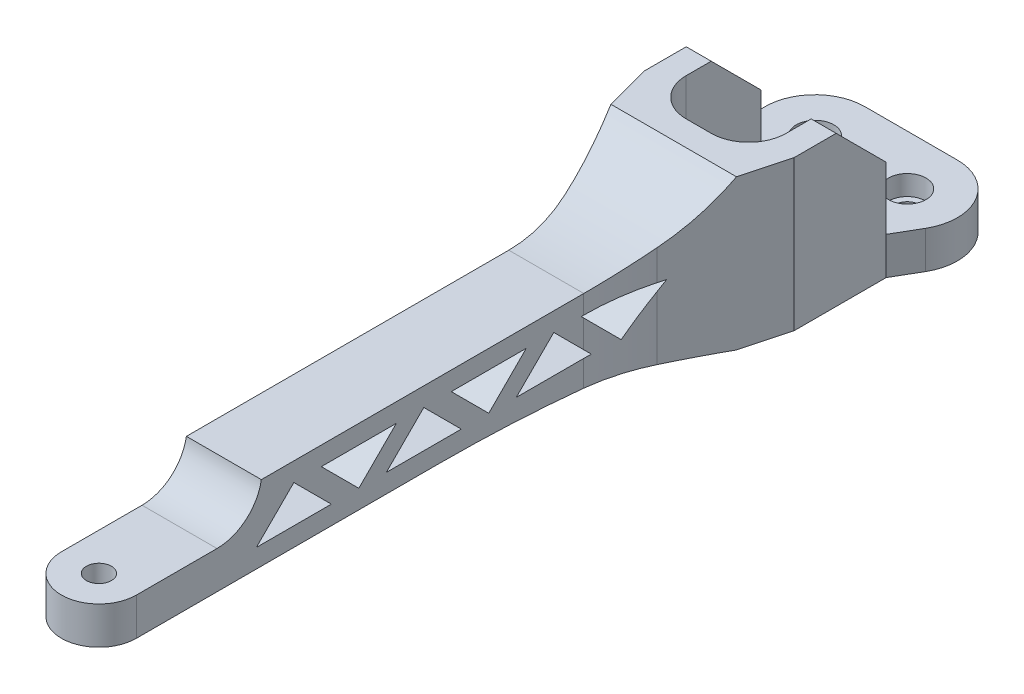
SolidWorks part; units mm, degrees
ref_plane "Front Plane" through (0, 0, 0) normal (0, 0, 1) x (1, 0, 0)
ref_plane "Top Plane" through (0, 0, 0) normal (0, 1, 0) x (1, 0, 0)
ref_plane "Right Plane" through (0, 0, 0) normal (1, 0, 0) x (0, 0, -1)
sketch "Sketch1" plane through (0, 0, 0) normal (1, 0, 0) x (0, 0, -1)
  line L0 (0, 0) -> (0, 15)
  line L1 (0, 15) -> (47.2518, 15)
  line L2 (65, 30) -> (194.0098, 30)
  line L3 (245, 50) -> (280, 50)
  line L4 (280, 50) -> (300, 30)
  line L5 (300, 30) -> (300, -10)
  line L6 (300, -10) -> (245, -10)
  line L7 (135.9129, 0) -> (0, 0)
  line L8 (63, 7.5) -> (78, 22.5)
  line L9 (78, 22.5) -> (93, 7.5)
  line L10 (93, 7.5) -> (63, 7.5)
  line L11 (104, 7.5) -> (89, 22.5)
  line L12 (89, 22.5) -> (119, 22.5)
  line L13 (119, 22.5) -> (104, 7.5)
  line L14 (171, 22.5) -> (156, 7.5)
  line L15 (156, 7.5) -> (141, 22.5)
  line L16 (141, 22.5) -> (171, 22.5)
  line L17 (145, 7.5) -> (115, 7.5)
  line L18 (115, 7.5) -> (130, 22.5)
  line L19 (130, 22.5) -> (145, 7.5)
  line L20 (223, 22.5) -> (208, 7.5)
  line L21 (208, 7.5) -> (193, 22.5)
  line L22 (193, 22.5) -> (223, 22.5)
  line L23 (197, 7.5) -> (167, 7.5)
  line L24 (167, 7.5) -> (182, 22.5)
  line L25 (182, 22.5) -> (197, 7.5)
  line L26 (119, 22.5) -> (171, 22.5) construction
  arc A0 (47.2518, 15) -> (65, 30) centre (47.2518, 33) ccw
  arc A1 (194.0098, 30) -> (245, 50) centre (194.0098, 105) ccw
  arc A3 (245, -10) -> (135.9129, 0) centre (135.9129, -600) ccw
  point P16 (0, 7.5)
  dimension "D2" = 18
  dimension "D5" = 75
  dimension "D12" = 600
  dimension "D1" = 65
  dimension "D3" = 15
  dimension "D4" = 30
  dimension "D6" = 245
  dimension "D7" = 60
  dimension "D8" = 300
  dimension "D9" = 20
  dimension "D10" = 45
  dimension "D11" = 10
  dimension "D13" = 45
  dimension "D14" = 63
  dimension "D15" = 30
  dimension "D16" = 11
  dimension "D18" = 11
  dimension "D17" = 3
extrude "Boss-Extrude1" add sketch "Sketch1" along normal mid plane 60
sketch "Sketch2" plane through (0, 0, 0) normal (0, 1, 0) x (1, 0, 0)
  line L0 (0, 0) -> (0, 300) construction
  line L1 (30, 0) -> (-30, 0) construction
  line L2 (30, 300) -> (-30, 300) construction
  line L3 (-15, 15) -> (-15, 194)
  line L4 (15, 15) -> (15, 194)
  line L5 (-18.4074, 219.8819) -> (-30, 263.146)
  line L6 (18.4074, 219.8819) -> (30, 263.146)
  line L7 (-30, 263.146) -> (-30, 300)
  line L8 (30, 263.146) -> (30, 300)
  line L9 (-30, 300) -> (-100, 300)
  line L10 (-100, 300) -> (-100, 0)
  line L11 (-100, 0) -> (0, 0)
  line L12 (30, 300) -> (100, 300)
  line L13 (-20, 300) -> (-20, 270)
  line L14 (100, 300) -> (100, 0)
  line L15 (100, 0) -> (0, 0)
  line L16 (-5, 255) -> (0, 255)
  line L17 (20, 300) -> (20, 270)
  line L18 (5, 255) -> (0, 255)
  line L19 (-20, 300) -> (20, 300)
  arc A0 (0, 0) -> (-15, 15) centre (0, 15) cw
  arc A1 (0, 0) -> (15, 15) centre (0, 15) ccw
  arc A2 (-15, 194) -> (-18.4074, 219.8819) centre (-115, 194) ccw
  arc A3 (15, 194) -> (18.4074, 219.8819) centre (115, 194) cw
  circle A5 centre (0, 15) radius 5
  arc A6 (-20, 270) -> (-5, 255) centre (-5, 270) ccw
  arc A7 (20, 270) -> (5, 255) centre (5, 270) cw
  dimension "D2" = 10
  dimension "D4" = 100
  dimension "D10" = 15
  dimension "D1" = 30
  dimension "D3" = 165
  dimension "D5" = 60
  dimension "D6" = 179
  dimension "D7" = 200
  dimension "D8" = 40
  dimension "D9" = 45
extrude "Cut-Extrude1" cut sketch "Sketch2" against normal through all both and the other way through all contours A3 L4 A1 L15 L14 L12 L8 L6 | L3 A2 L5 L7 L9 L10 L11 A0 | L19 L17 A7 L18 L16 A6 L13 | A5
sketch "Sketch3" plane through (0, 0, 0) normal (0, 1, 0) x (1, 0, 0)
  line L0 (-20, 270) -> (-20, 280) construction
  line L1 (-20, 280) -> (-20, 300) construction
  line L2 (20, 280) -> (20, 300) construction
  line L3 (20, 270) -> (20, 280) construction
  line L4 (-5, 255) -> (5, 255) construction
  line L5 (-20, 270) -> (-20, 280)
  line L6 (-20, 280) -> (-20, 300)
  line L7 (20, 280) -> (20, 300)
  line L8 (20, 270) -> (20, 280)
  line L9 (-5, 255) -> (5, 255)
  line L10 (0, 255) -> (0, 340) construction
  line L11 (-20, 300) -> (-30, 300)
  line L12 (20, 300) -> (30, 300)
  line L13 (-30, 300) -> (-35.7851, 309.9389)
  line L14 (30, 300) -> (35.7851, 309.9389)
  line L15 (-18.5, 340) -> (0, 340)
  line L16 (18.5, 340) -> (0, 340)
  arc A0 (-20, 270) -> (-5, 255) centre (-5, 270) ccw construction
  arc A1 (5, 255) -> (20, 270) centre (5, 270) ccw construction
  arc A2 (-20, 270) -> (-5, 255) centre (-5, 270) ccw
  arc A3 (5, 255) -> (20, 270) centre (5, 270) ccw
  arc A4 (-35.7851, 309.9389) -> (-18.5, 340) centre (-18.5, 320) cw
  arc A5 (35.7851, 309.9389) -> (18.5, 340) centre (18.5, 320) ccw
  circle A6 centre (0, 15) radius 5 construction
  dimension "D1" = 77
  dimension "D2" = 20
  dimension "D3" = 325
extrude "Boss-Extrude2" add sketch "Sketch3" along normal blind 15 from surface at -10 starting at face at (0, -10, -271.6732)
sketch "Sketch6" plane through (0, 5, 0) normal (0, 1, 0) x (1, 0, 0)
  line L0 (-30, 300) -> (-30, 280) construction
  line L1 (18.5, 340) -> (-18.5, 340) construction
  line L2 (-18.45, 320) -> (18.45, 320) construction
  point P0 (0, 280)
  point P2 (-18.45, 320)
  point P4 (18.45, 320)
  point P16 (0, 320)
  dimension "D1" = 30
  dimension "D2" = 36.9
  dimension "D4" = 20
  dimension "D5" = 60
hole_wizard "CBORE for M10 Hex Head Bolt1" positions "Sketch6" profile "Sketch5" counterbore size "M10" standard "DIN" end condition through all
sketch "Sketch5" plane through (0, 5, -280) normal (1, 0, 0) x (0, 0, 1)
  line L0 (0, 0) -> (0, 15)
  line L1 (0, 15) -> (5, 15)
  line L3 (5, 15) -> (5, 8)
  line L4 (5, 8) -> (7.5, 8)
  line L5 (7.5, 8) -> (7.5, 0)
  line L7 (7.5, 0) -> (0, 0)
  line L11 (0, -6.35) -> (0, 107.95) construction
  dimension "Thru Hole Dia." = 10
  dimension "Thru Hole Depth" = 15
  dimension "C'Bore Dia." = 15
  dimension "C'Bore Depth" = 8
